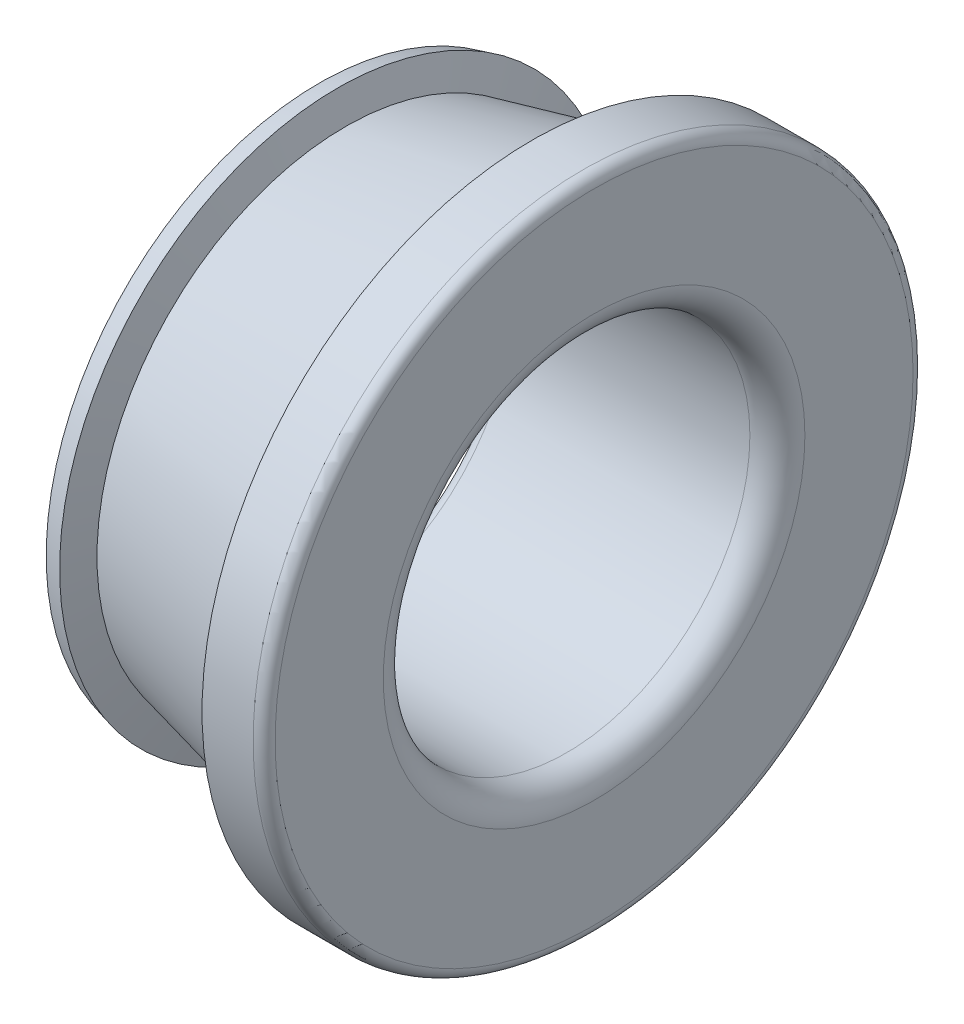
SolidWorks part; units mm, degrees
ref_plane "Plan1" through (0, 0, 0) normal (0, 0, 1) x (1, 0, 0)
ref_plane "Plan2" through (0, 0, 0) normal (0, 1, 0) x (1, 0, 0)
ref_plane "Plan3" through (0, 0, 0) normal (1, 0, 0) x (0, 0, -1)
sketch "Esquisse1" plane through (0, 0, 0) normal (0, 0, 1) x (1, 0, 0)
  line L0 (0, 0) -> (-29.1339, 0) construction
  line L1 (0, 11.5) -> (0, 17.4)
  line L2 (-1.5, 10) -> (-14.4, 10)
  line L3 (-15, 10.6) -> (-15, 14.8879)
  line L4 (-15, 14.8879) -> (-14, 15.1559)
  line L5 (-3.3856, 18) -> (-2.868, 16.0681)
  line L6 (-14, 15.1559) -> (-13.5693, 13.5483)
  line L7 (-2.868, 16.0681) -> (-13.5693, 13.5483)
  line L8 (-3.3856, 18) -> (-0.6, 18)
  arc A0 (0, 11.5) -> (-1.5, 10) centre (-1.5, 11.5) cw
  arc A1 (-14.4, 10) -> (-15, 10.6) centre (-14.4, 10.6) cw
  arc A2 (0, 17.4) -> (-0.6, 18) centre (-0.6, 17.4) ccw
  point P9 (0, 10)
  point P12 (-15, 10)
  point P17 (0, 18)
  dimension "D5" = 1.5
  dimension "D10" = 0.6
  dimension "D11" = 0.6
  dimension "D1" = 15
  dimension "D2" = 10
  dimension "D3" = 18
  dimension "D4" = 15
  dimension "D6" = 13.25
  dimension "D7" = 2
  dimension "D8" = 3.3856
  dimension "D9" = 1
revolve "Base-Révolution" add sketch "Esquisse1" angle 360 about L0
